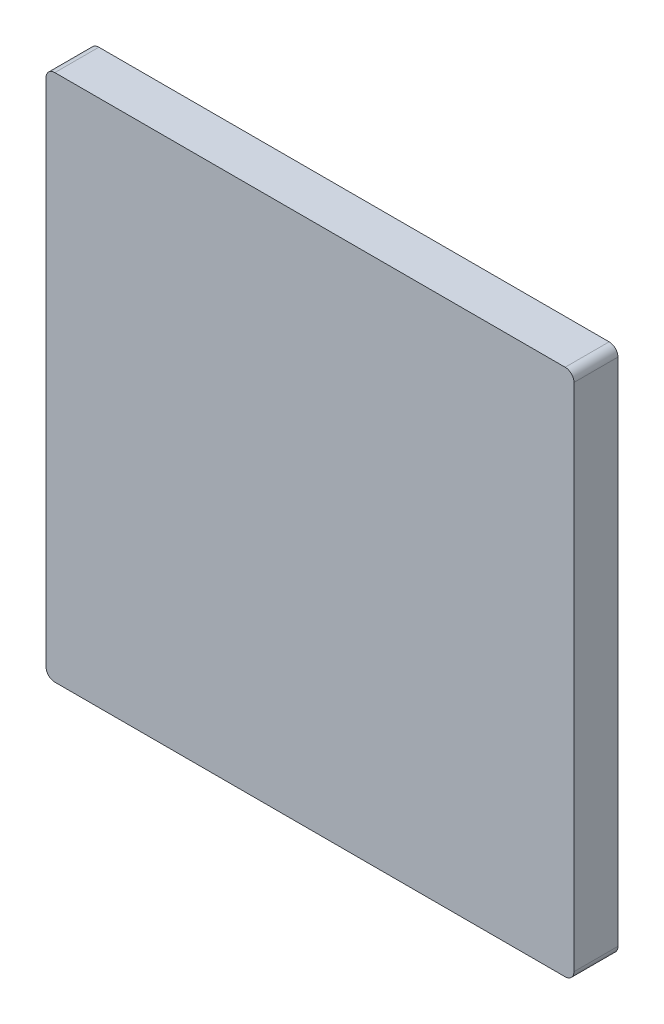
SolidWorks part; units mm, degrees
material "硅"
ref_plane "前视基准面" through (0, 0, 0) normal (0, 0, 1) x (1, 0, 0)
ref_plane "上视基准面" through (0, 0, 0) normal (0, 1, 0) x (1, 0, 0)
ref_plane "右视基准面" through (0, 0, 0) normal (1, 0, 0) x (0, 0, -1)
sketch "草图1" plane through (0, 0, 0) normal (0, 0, 1) x (1, 0, 0)
  line L1 (-4.8963, 5.3478) -> (1.1037, 5.3478)
  line L2 (-4.8963, 5.3478) -> (-4.8963, -0.6522)
  line L3 (-4.8963, -0.6522) -> (1.1037, -0.6522)
  line L4 (1.1037, 5.3478) -> (1.1037, -0.6522)
  dimension "D1" = 6
  dimension "D2" = 6
extrude "凸台-拉伸1" add sketch "草图1" along normal blind 0.5
fillet "圆角1" radius 0.1 4 edges at (-4.8963, 5.3478, 0.25) (1.1037, 5.3478, 0.25) (1.1037, -0.6522, 0.25) (-4.8963, -0.6522, 0.25)
